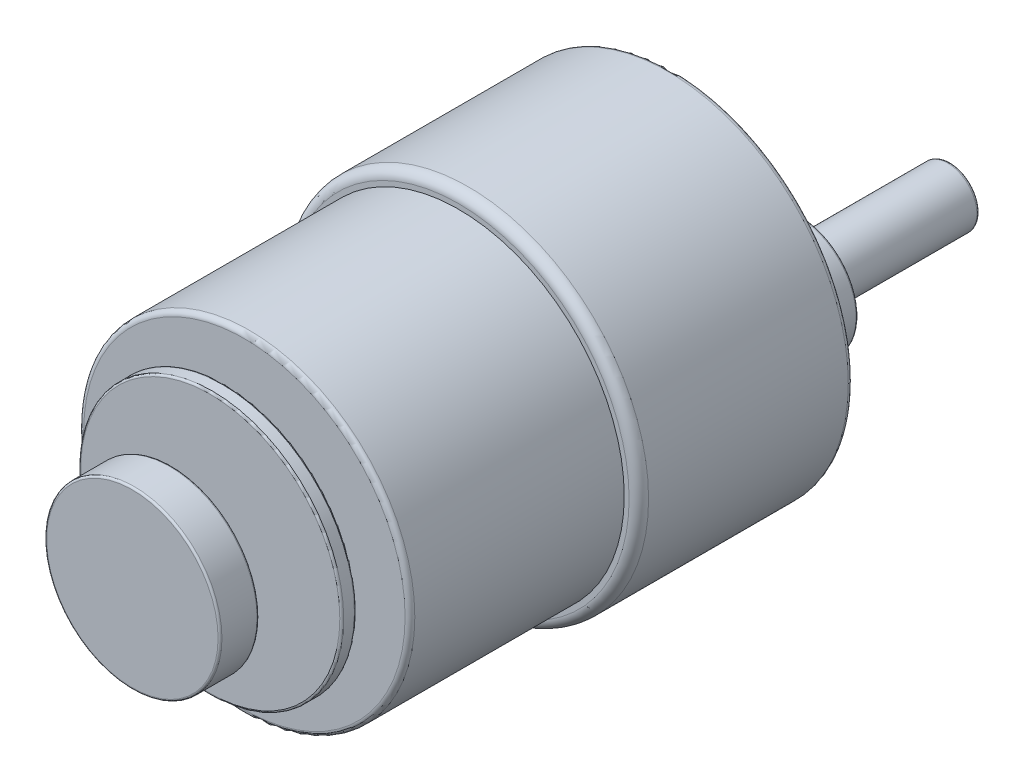
SolidWorks part; units mm, degrees
ref_plane "前视基准面" through (0, 0, 0) normal (0, 0, 1) x (1, 0, 0)
ref_plane "上视基准面" through (0, 0, 0) normal (0, 1, 0) x (1, 0, 0)
ref_plane "右视基准面" through (0, 0, 0) normal (1, 0, 0) x (0, 0, -1)
sketch "草图1" plane through (0, 0, 0) normal (0, 0, 1) x (1, 0, 0)
  circle A0 centre (0, 0) radius 17
  dimension "D1" = 34
extrude "凸台-拉伸2" add sketch "草图1" along normal blind 22 contours A0
sketch "草图3" plane through (0, 0, 0) normal (0, 0, -1) x (-1, 0, 0)
  circle A0 centre (0, 0) radius 18.5
  dimension "D1" = 37
extrude "凸台-拉伸4" add sketch "草图3" along normal blind 22
sketch "草图4" plane through (0, 0, -22) normal (0, 0, -1) x (-1, 0, 0)
  circle A0 centre (-7, 0) radius 6
extrude "凸台-拉伸5" add sketch "草图4" along normal blind 6
sketch "草图5" plane through (0, 0, -28) normal (0, 0, -1) x (-1, 0, 0)
  circle A0 centre (-7, 0) radius 3
extrude "凸台-拉伸6" add sketch "草图5" along normal blind 15.5
sketch "草图14" plane through (0, 0, 22) normal (0, 0, 1) x (1, 0, 0)
  circle A0 centre (0, 0) radius 3
extrude "凸台-拉伸7" add sketch "草图14" along normal blind 2
sketch "草图16" plane through (0, 0, 24) normal (0, 0, 1) x (1, 0, 0)
  circle A0 centre (0, 0) radius 13.5
extrude "凸台-拉伸8" add sketch "草图16" along normal blind 1.5
sketch "草图17" plane through (0, 0, 25.5) normal (0, 0, 1) x (1, 0, 0)
  circle A0 centre (0, 0) radius 1
extrude "凸台-拉伸9" add sketch "草图17" along normal blind 4
sketch "草图18" plane through (0, 0, 29.5) normal (0, 0, 1) x (1, 0, 0)
  circle A0 centre (0, 0) radius 9
extrude "凸台-拉伸10" add sketch "草图18" along normal blind 4
fillet "圆角2" radius 0.5 1 edges at (17, 0, 22)
fillet "圆角3" radius 0.5 1 edges at (-18.5, 0, -22)
fillet "圆角4" radius 0.2 1 edges at (13.5, 0, 25.5)
fillet "圆角5" radius 0.2 1 edges at (13.5, 0, 24)
fillet "圆角6" radius 0.2 1 edges at (9, 0, 33.5)
fillet "圆角7" radius 0.2 1 edges at (9, 0, 29.5)
fillet "圆角8" radius 0.2 1 edges at (1, 0, -28)
fillet "圆角9" radius 0.3 1 edges at (4, 0, -43.5)
fillet "圆角10" radius 1 1 edges at (-18.5, 0, 0)
